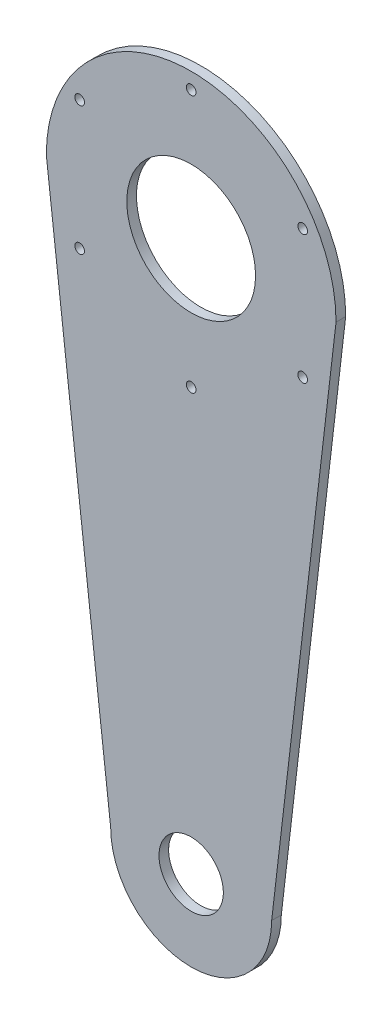
SolidWorks part; units mm, degrees
ref_plane "Front Plane" through (0, 0, 0) normal (0, 0, 1) x (1, 0, 0)
ref_plane "Top Plane" through (0, 0, 0) normal (0, 1, 0) x (1, 0, 0)
ref_plane "Right Plane" through (0, 0, 0) normal (1, 0, 0) x (0, 0, -1)
sketch "Sketch1" plane through (0, 0, 0) normal (0, 0, 1) x (1, 0, 0)
  line L1 (-45, 0) -> (-25, -171)
  line L2 (45, 0) -> (25, -171)
  line L3 (0, -161) -> (-69.3545, -161) construction
  line L4 (-80, -240.7502) -> (80, -240.7502) construction
  line L5 (-80, -240.7502) -> (-80, 79.2498) construction
  line L6 (-80, 79.2498) -> (80, 79.2498) construction
  line L7 (80, -240.7502) -> (80, 79.2498) construction
  line L8 (-80, -240.7502) -> (80, 79.2498) construction
  line L9 (-80, 79.2498) -> (80, -240.7502) construction
  arc A0 (43.7855, -10.3843) -> (-43.7855, -10.3843) centre (0, 0) ccw
  arc A1 (-25, -171) -> (25, -171) centre (0, -171) ccw
  circle A2 centre (0, -171) radius 10
  circle A3 centre (0, 0) radius 20
  circle A4 centre (0, 0) radius 40 construction
  circle A5 centre (0, 40) radius 1.5
  circle A6 centre (34.641, 20) radius 1.5
  circle A7 centre (34.641, -20) radius 1.5
  circle A8 centre (0, -40) radius 1.5
  circle A9 centre (-34.641, -20) radius 1.5
  circle A10 centre (-34.641, 20) radius 1.5
  point P13 (0, -80.7502)
  point P33 (0, 0)
  dimension "D2" = 90
  dimension "D3" = 25
  dimension "D5" = 20
  dimension "D6" = 40
  dimension "D8" = 80
  dimension "D10" = 3
  dimension "D1" = 161
  dimension "D4" = 320
  dimension "D7" = 160
  dimension "D9" = 6
extrude "Boss-Extrude1" add sketch "Sketch1" along normal blind 3 contours L1 A1 L2 A0 A3 A2
